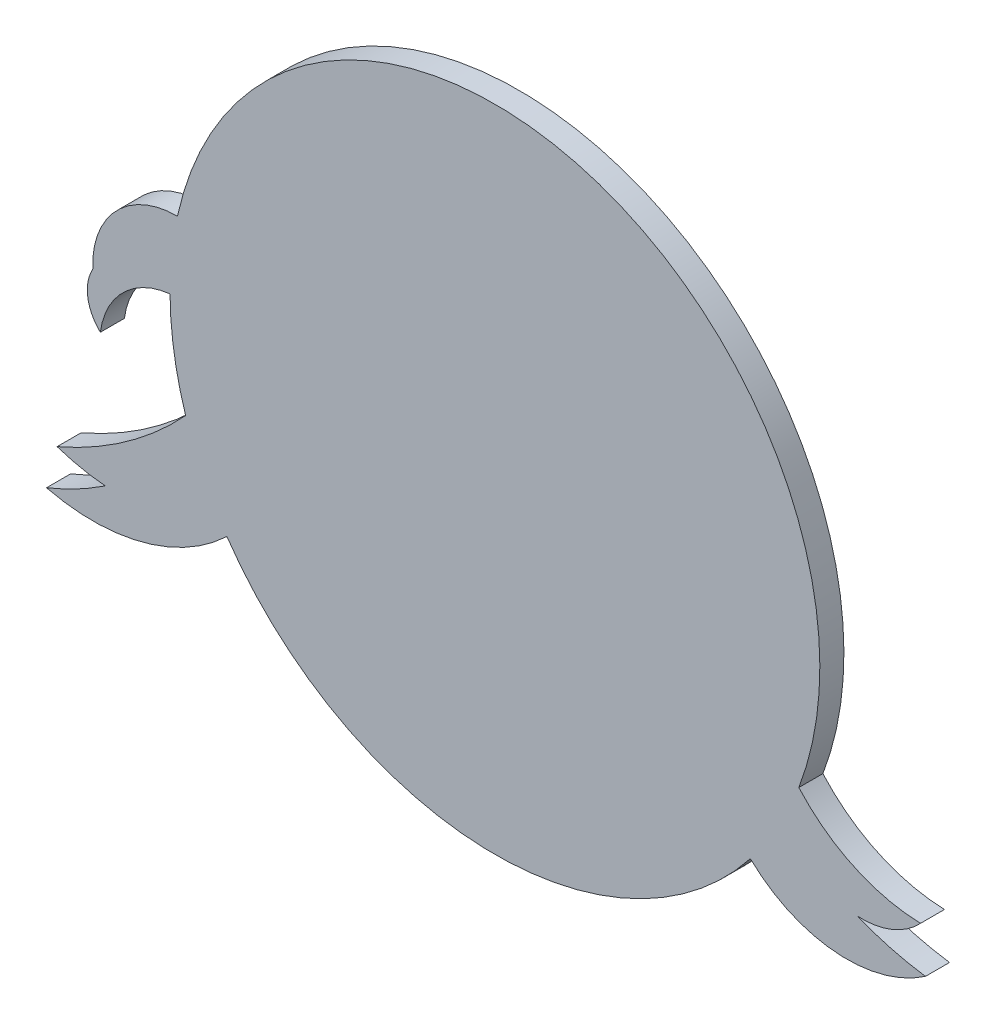
SolidWorks part; units mm, degrees
ref_plane "Front Plane" through (0, 0, 0) normal (0, 0, 1) x (1, 0, 0)
ref_plane "Top Plane" through (0, 0, 0) normal (0, 1, 0) x (1, 0, 0)
ref_plane "Right Plane" through (0, 0, 0) normal (1, 0, 0) x (0, 0, -1)
sketch "Sketch1" plane through (0, 0, 0) normal (0, 0, 1) x (1, 0, 0)
  arc A0 (-33.4154, -22.8836) -> (31.8377, -25.0321) centre (0, 0) ccw
  arc A5 (37.8791, -14.3325) -> (-39.5729, 8.6162) centre (0, 0) ccw
  arc A6 (-55.8999, -28.8639) -> (-33.4154, -22.8836) centre (-50.1343, -5.2826) ccw
  arc A7 (-55.8999, -28.8639) -> (-48.5729, -25) centre (-70.4185, 7.5462) ccw
  arc A8 (-48.5729, -25) -> (-54.5792, -23.7641) centre (-46.4975, 0.2981) cw
  arc A9 (-54.5792, -23.7641) -> (-38.5562, -12.3964) centre (-73.219, 19.4856) ccw
  arc A10 (31.8377, -25.0321) -> (53.661, -26.8287) centre (43.8511, -12.5479) ccw
  arc A11 (53.661, -26.8287) -> (45.1374, -24.5558) centre (58.8656, 9.8069) cw
  arc A13 (53.0386, -21.4169) -> (37.8791, -14.3325) centre (53.7016, -0.2367) cw
  arc A14 (45.1374, -24.5558) -> (53.0386, -21.4169) centre (45.7421, -14.5639) ccw
  arc A15 (-40.4993, -0.2367) -> (-49.1864, -8.7211) centre (-39.4447, -10.006) ccw
  arc A16 (-39.5729, 8.6162) -> (-50.1343, -2.398) centre (-39.606, -1.9228) ccw
  arc A17 (-50.1343, -2.398) -> (-49.1864, -8.7211) centre (-45.6304, -4.9554) ccw
  arc A18 (-40.4993, -0.2367) -> (-38.5562, -12.3964) centre (0, 0) ccw
  point P27 (-49.229, -8.7812)
  point P28 (-49.1864, -8.7211)
  point P29 (-49.7193, -2.6665)
  point P30 (-50.1343, -2.398)
  dimension "D1" = 81
extrude "Boss-Extrude1" add sketch "Sketch1" along normal blind 3
